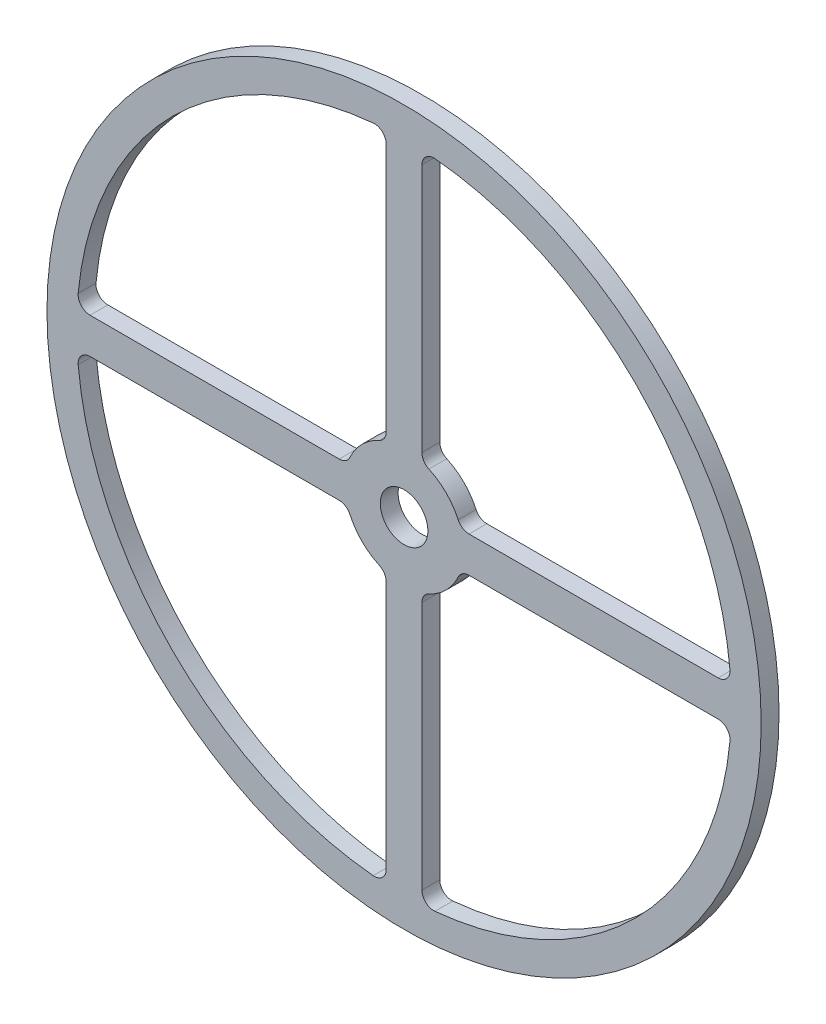
SolidWorks part; units mm, degrees
ref_plane "前视基准面" through (0, 0, 0) normal (0, 0, 1) x (1, 0, 0)
ref_plane "上视基准面" through (0, 0, 0) normal (0, 1, 0) x (1, 0, 0)
ref_plane "右视基准面" through (0, 0, 0) normal (1, 0, 0) x (0, 0, -1)
sketch "草图1" plane through (0, 0, 0) normal (0, 0, 1) x (1, 0, 0)
  line L0 (3, 54.9181) -> (3, 9.5394)
  line L1 (9.5394, 3) -> (54.9181, 3)
  line L2 (0, 72.2615) -> (0, -79.5295) construction
  line L3 (-78.2791, 0) -> (88.2263, 0) construction
  line L4 (-9.5394, -3) -> (-54.9181, -3)
  line L5 (9.5394, -3) -> (54.9181, -3)
  line L7 (-3, 9.5394) -> (-3, 54.9181)
  line L8 (-3, -9.5394) -> (-3, -54.9181)
  line L9 (3, -9.5394) -> (3, -54.9181)
  line L10 (-9.5394, 3) -> (-54.9181, 3)
  circle A0 centre (0, 0) radius 60
  arc A1 (-3, 54.9181) -> (-54.9181, 3) centre (0, 0) ccw
  arc A2 (3, -54.9181) -> (54.9181, -3) centre (0, 0) ccw
  arc A3 (-54.9181, -3) -> (-3, -54.9181) centre (0, 0) ccw
  arc A4 (54.9181, 3) -> (3, 54.9181) centre (0, 0) ccw
  arc A5 (-3, 9.5394) -> (-9.5394, 3) centre (0, 0) ccw
  circle A6 centre (0, 0) radius 4
  arc A7 (9.5394, 3) -> (3, 9.5394) centre (0, 0) ccw
  arc A8 (-9.5394, -3) -> (-3, -9.5394) centre (0, 0) ccw
  arc A9 (3, -9.5394) -> (9.5394, -3) centre (0, 0) ccw
  dimension "D1" = 120
  dimension "D2" = 110
  dimension "D5" = 8
  dimension "D6" = 20
  dimension "D3" = 3
  dimension "D4" = 3
extrude "凸台-拉伸1" add sketch "草图1" along normal blind 3
fillet "圆角1" radius 2 1 edges at (3, 54.9181, 1.5)
fillet "圆角2" radius 2 7 edges at (54.9181, 3, 1.5) (54.9181, -3, 1.5) (3, -54.9181, 1.5) (-3, -54.9181, 1.5) (-54.9181, -3, 1.5) (-54.9181, 3, 1.5) (-3, 54.9181, 1.5)
fillet "圆角4" radius 2 8 edges at (3, -9.5394, 1.5) (-3, -9.5394, 1.5) (-9.5394, -3, 1.5) (-9.5394, 3, 1.5) (-3, 9.5394, 1.5) (3, 9.5394, 1.5) (9.5394, 3, 1.5) (9.5394, -3, 1.5)
